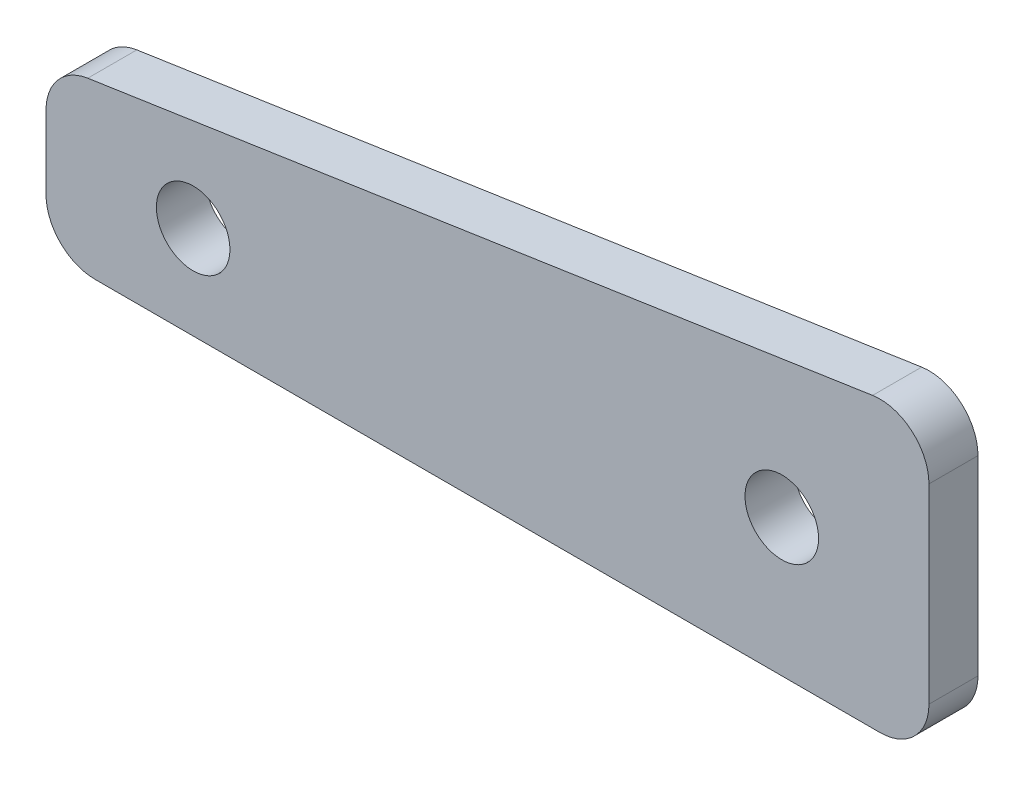
SolidWorks part; units mm, degrees
ref_plane "Front Plane" through (0, 0, 0) normal (0, 0, 1) x (1, 0, 0)
ref_plane "Top Plane" through (0, 0, 0) normal (0, 1, 0) x (1, 0, 0)
ref_plane "Right Plane" through (0, 0, 0) normal (1, 0, 0) x (0, 0, -1)
sketch "Sketch1" plane through (0, 0, 0) normal (0, 0, 1) x (1, 0, 0)
  line L3 (-349.721, 11.0419) -> (-298.921, 18.6619)
  line L11 (-304.8, 0) -> (-304.8, 17.78)
  line L12 (-342.9, 0) -> (-342.9, 12.065)
  line L13 (-352.425, 7.902) -> (-352.425, 3.175)
  line L14 (-295.275, 3.175) -> (-295.275, 15.522)
  line L15 (-298.45, 0) -> (-349.25, 0)
  circle A0 centre (-342.9, 6.0325) radius 2.3813
  circle A1 centre (-304.8, 8.89) radius 2.3813
  arc A2 (-295.275, 15.522) -> (-298.921, 18.6619) centre (-298.45, 15.522) ccw
  arc A3 (-295.275, 3.175) -> (-298.45, 0) centre (-298.45, 3.175) cw
  arc A4 (-352.425, 3.175) -> (-349.25, 0) centre (-349.25, 3.175) ccw
  arc A5 (-352.425, 7.902) -> (-349.721, 11.0419) centre (-349.25, 7.902) cw
  dimension "D9" = 4.7625
  dimension "D10" = 4.7625
  dimension "D2" = 3.175
  dimension "D7" = 9.525
  dimension "D8" = 9.525
extrude "Boss-Extrude1" add sketch "Sketch1" along normal blind 3.175 contours A5 L13 A4 L15 L12 A0 L3 | A1 L11 L3 L12 A0 L15 | A3 L14 A2 L3 L11 A1 L15
